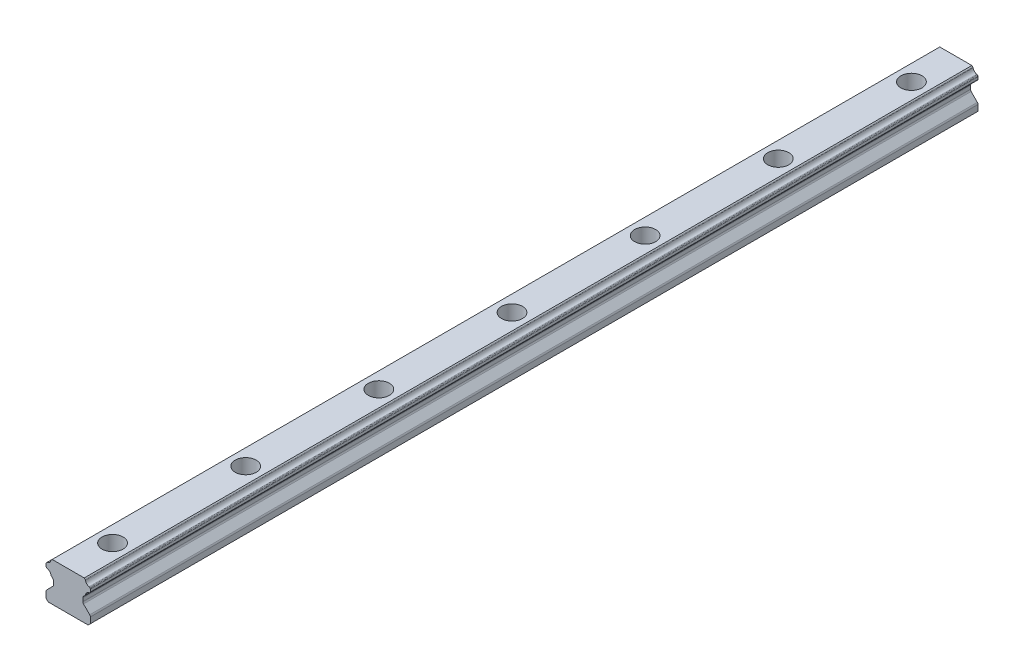
SolidWorks part; units mm, degrees
material "45#"
ref_plane "前视" through (0, 0, 0) normal (0, 0, 1) x (1, 0, 0)
ref_plane "上视" through (0, 0, 0) normal (0, 1, 0) x (1, 0, 0)
ref_plane "右视" through (0, 0, 0) normal (1, 0, 0) x (0, 0, -1)
sketch "草图1" plane through (0, 0, 0) normal (0, 0, 1) x (1, 0, 0)
  line L0 (0.1464, 14.8772) -> (0.3367, 15.0674)
  line L1 (0, 13.4664) -> (0, 14.5236)
  line L2 (0.3247, 12.9346) -> (0.1464, 13.1128)
  line L3 (3.1071, 10.1522) -> (2.3546, 10.9047)
  line L4 (3.4, 7.8849) -> (3.4, 9.4451)
  line L5 (3.1071, 7.1778) -> (0.2929, 4.3636)
  line L6 (0, 3.6565) -> (0, 1)
  line L7 (1, 0) -> (0, 1)
  line L8 (19, 0) -> (1, 0)
  line L9 (19, 0) -> (20, 1)
  line L10 (20, 1) -> (20, 3.6565)
  line L11 (19.7071, 4.3636) -> (16.8929, 7.1778)
  line L12 (16.6, 9.4451) -> (16.6, 7.8849)
  line L13 (17.6454, 10.9047) -> (16.8929, 10.1522)
  line L14 (19.8536, 13.1128) -> (19.6753, 12.9346)
  line L15 (20, 14.5236) -> (20, 13.4664)
  line L16 (19.6633, 15.0674) -> (19.8536, 14.8772)
  line L17 (17.2307, 17.5) -> (17.6477, 17.083)
  line L18 (17.2307, 17.5) -> (2.7693, 17.5)
  line L19 (2.3523, 17.083) -> (2.7693, 17.5)
  arc A0 (0.5973, 15.2051) -> (0.3367, 15.0674) centre (0.6902, 14.7138) ccw
  arc A1 (0.5973, 15.2051) -> (2.2146, 16.8224) centre (0.22, 17.1997) ccw
  arc A2 (0.1464, 14.8772) -> (0, 14.5236) centre (0.5, 14.5236) ccw
  arc A3 (0, 13.4664) -> (0.1464, 13.1128) centre (0.5, 13.4664) ccw
  arc A4 (0.3247, 12.9346) -> (0.5876, 12.7964) centre (0.6782, 13.2882) ccw
  arc A5 (2.2164, 11.1677) -> (0.5876, 12.7964) centre (0.22, 10.8) ccw
  arc A6 (2.2164, 11.1677) -> (2.3546, 10.9047) centre (2.7081, 11.2583) ccw
  arc A7 (3.4, 9.4451) -> (3.1071, 10.1522) centre (2.4, 9.4451) ccw
  arc A8 (3.1071, 7.1778) -> (3.4, 7.8849) centre (2.4, 7.8849) ccw
  arc A9 (0.2929, 4.3636) -> (0, 3.6565) centre (1, 3.6565) ccw
  arc A10 (20, 3.6565) -> (19.7071, 4.3636) centre (19, 3.6565) ccw
  arc A11 (16.6, 7.8849) -> (16.8929, 7.1778) centre (17.6, 7.8849) ccw
  arc A12 (16.8929, 10.1522) -> (16.6, 9.4451) centre (17.6, 9.4451) ccw
  arc A13 (17.6454, 10.9047) -> (17.7836, 11.1677) centre (17.2919, 11.2583) ccw
  arc A14 (19.4124, 12.7964) -> (17.7836, 11.1677) centre (19.78, 10.8) ccw
  arc A15 (19.4124, 12.7964) -> (19.6753, 12.9346) centre (19.3218, 13.2882) ccw
  arc A16 (19.8536, 13.1128) -> (20, 13.4664) centre (19.5, 13.4664) ccw
  arc A17 (20, 14.5236) -> (19.8536, 14.8772) centre (19.5, 14.5236) ccw
  arc A18 (19.6633, 15.0674) -> (19.4027, 15.2051) centre (19.3098, 14.7138) ccw
  arc A19 (17.7854, 16.8224) -> (19.4027, 15.2051) centre (19.78, 17.1997) ccw
  arc A20 (17.7854, 16.8224) -> (17.6477, 17.083) centre (17.2941, 16.7295) ccw
  arc A21 (2.3523, 17.083) -> (2.2146, 16.8224) centre (2.7059, 16.7295) ccw
extrude "凸台-拉伸1" add sketch "草图1" against normal blind 400
hole_wizard "打孔尺寸根据内六角圆柱头螺钉的类型1" positions "草图3" profile "草图2" counterbore size "M5" standard "Gb" end condition through all
sketch "草图3" plane through (0, 17.5, 0) normal (0, 1, 0) x (1, 0, 0)
  line L0 (10, 0) -> (10, 38.0317) construction
  line L1 (17.2307, 0) -> (2.7693, 0) construction
  point P0 (10, 20)
  dimension "D1" = 20
sketch "草图2" plane through (10, 17.5, -20) normal (1, 0, 0) x (0, 0, 1)
  line L0 (0, 0) -> (0, 17.5)
  line L1 (0, 17.5) -> (3, 17.5)
  line L3 (3, 17.5) -> (3, 8.5)
  line L4 (3, 8.5) -> (4.75, 8.5)
  line L5 (4.75, 8.5) -> (4.75, 0)
  line L7 (4.75, 0) -> (0, 0)
  line L11 (0, -6.35) -> (0, 107.95) construction
  dimension "通孔孔直径" = 6
  dimension "通孔孔深度" = 17.5
  dimension "柱形沉头孔直径" = 9.5
  dimension "柱形沉头孔深度" = 8.5
pattern_linear "阵列(线性)1" count 7 spacing 60 along (0, 0, -1) of "打孔尺寸根据内六角圆柱头螺钉的类型1"
